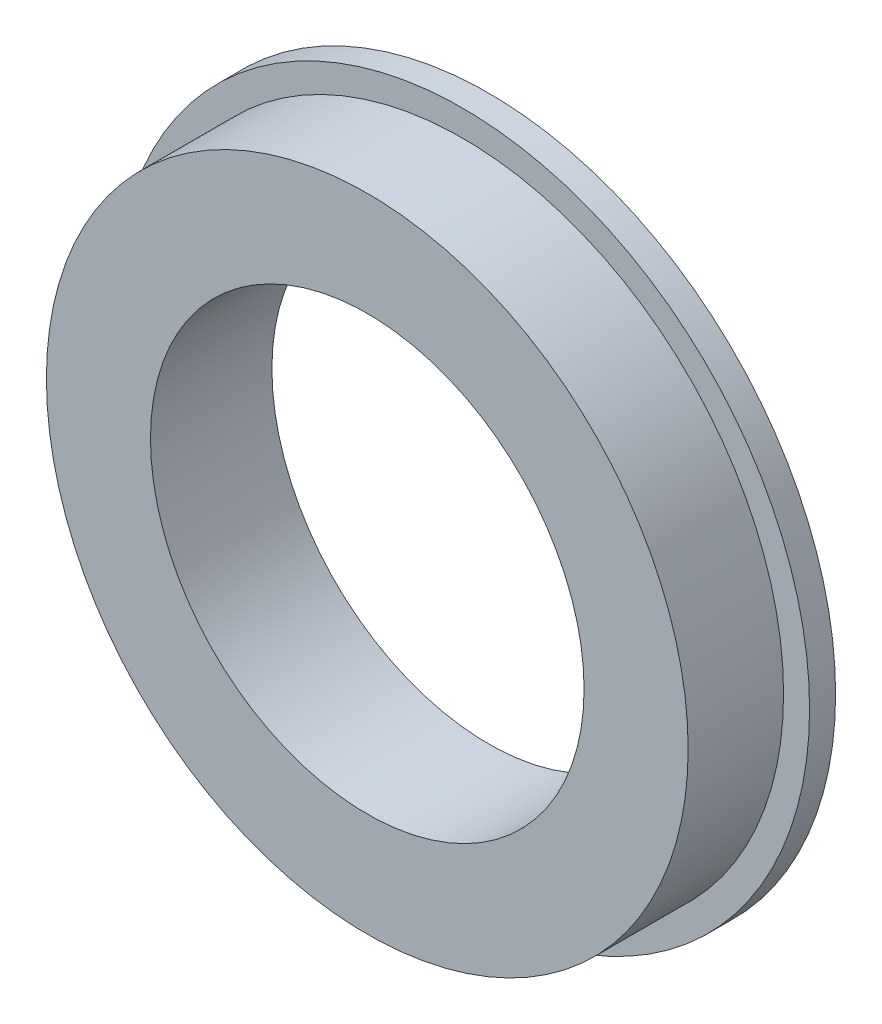
SolidWorks part; units mm, degrees
ref_plane "前视基准面" through (0, 0, 0) normal (0, 0, 1) x (1, 0, 0)
ref_plane "上视基准面" through (0, 0, 0) normal (0, 1, 0) x (1, 0, 0)
ref_plane "右视基准面" through (0, 0, 0) normal (1, 0, 0) x (0, 0, -1)
sketch "草图1" plane through (0, 0, 0) normal (0, 0, 1) x (1, 0, 0)
  circle A0 centre (0, 0) radius 18.5
  circle A1 centre (0, 0) radius 12.5
  dimension "D1" = 25
  dimension "D2" = 37
extrude "凸台-拉伸1" add sketch "草图1" along normal blind 5.5
sketch "草图2" plane through (0, 0, 0) normal (0, 0, -1) x (-1, 0, 0)
  circle A1 centre (0, 0) radius 20
  circle A2 centre (0, 0) radius 12.5
  dimension "D1" = 25
  dimension "D2" = 40
extrude "凸台-拉伸2" add sketch "草图2" along normal blind 1.5
